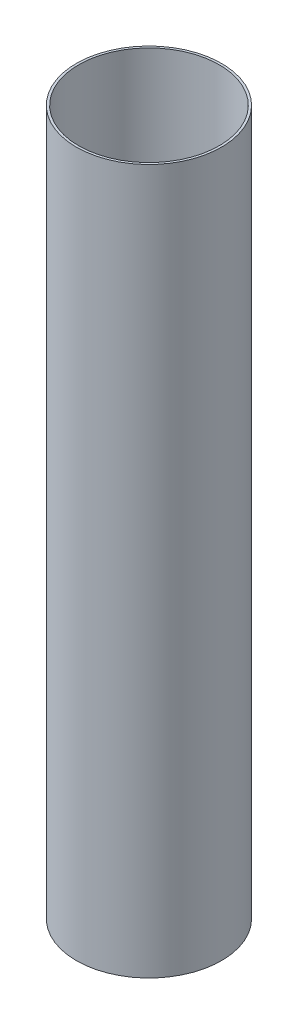
SolidWorks part; units mm, degrees
ref_plane "Front Plane" through (0, 0, 0) normal (0, 0, 1) x (1, 0, 0)
ref_plane "Top Plane" through (0, 0, 0) normal (0, 1, 0) x (1, 0, 0)
ref_plane "Right Plane" through (0, 0, 0) normal (1, 0, 0) x (0, 0, -1)
sketch "Sketch1" plane through (0, 0, 0) normal (0, 1, 0) x (1, 0, 0)
  circle A0 centre (0, 0) radius 78.5
  circle A1 centre (0, 0) radius 76
extrude "Boss-Extrude1" add sketch "Sketch1" along normal blind 762
